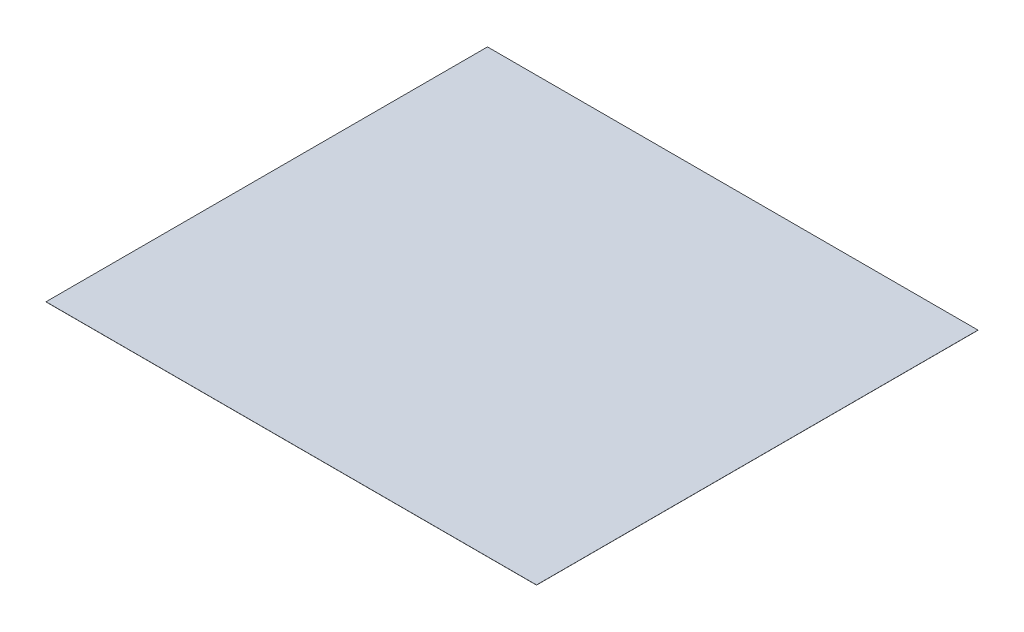
SolidWorks part; units mm, degrees
ref_plane "Front Plane" through (0, 0, 0) normal (0, 0, 1) x (1, 0, 0)
ref_plane "Top Plane" through (0, 0, 0) normal (0, 1, 0) x (1, 0, 0)
ref_plane "Right Plane" through (0, 0, 0) normal (1, 0, 0) x (0, 0, -1)
sketch "Sketch1" plane through (0, 0, 0) normal (0, 1, 0) x (1, 0, 0)
  line L0 (0, 160) -> (0, 0) construction
  line L1 (-220, 180) -> (180, 180)
  line L2 (-220, 180) -> (-220, -180)
  line L3 (-220, -180) -> (180, -180)
  line L4 (180, 180) -> (180, -180)
  line L5 (-160, 160) -> (160, 160) construction
  line L6 (-160, 160) -> (-160, -160) construction
  line L7 (-160, -160) -> (160, -160) construction
  line L8 (160, 160) -> (160, -160) construction
  line L9 (0, 0) -> (160, 0) construction
  line L10 (0, 0) -> (-160, 0) construction
  line L11 (0, 0) -> (0, -160) construction
  line L12 (-120, 160) -> (-120, -160) construction
  line L13 (-80, 160) -> (-80, -160) construction
  line L14 (-40, 160) -> (-40, -160) construction
  line L15 (0, 160) -> (0, -160) construction
  line L16 (40, 160) -> (40, -160) construction
  line L17 (80, 160) -> (80, -160) construction
  line L18 (120, 160) -> (120, -160) construction
  line L19 (-160, 120) -> (160, 120) construction
  line L20 (-160, 80) -> (160, 80) construction
  line L21 (-160, 40) -> (160, 40) construction
  line L22 (-160, 0) -> (160, 0) construction
  line L23 (-160, -40) -> (160, -40) construction
  line L24 (-160, -80) -> (160, -80) construction
  line L25 (-160, -120) -> (160, -120) construction
  dimension "D1" = 360
  dimension "D2" = 400
  dimension "D3" = 320
  dimension "D4" = 320
  dimension "D5" = 20
  dimension "D6" = 20
extrude "Boss-Extrude1" add sketch "Sketch1" along normal blind 0.1
